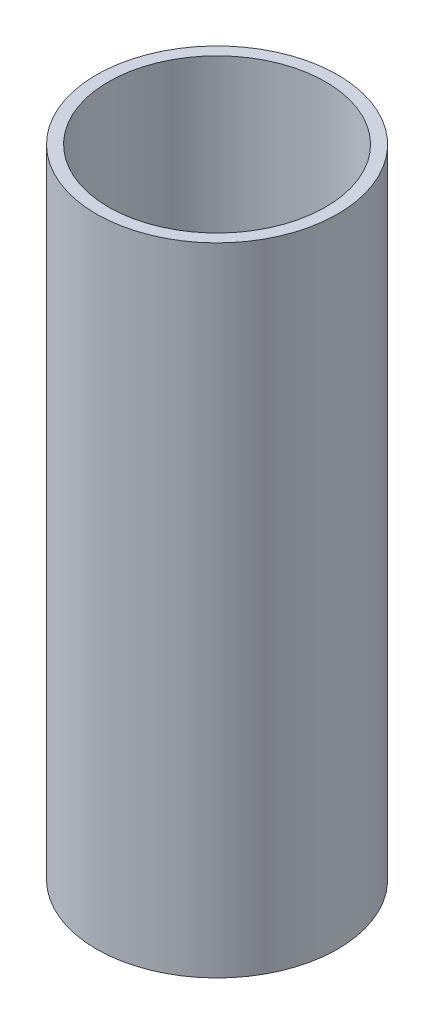
SolidWorks part; units mm, degrees
ref_plane "Front Plane" through (0, 0, 0) normal (0, 0, 1) x (1, 0, 0)
ref_plane "Top Plane" through (0, 0, 0) normal (0, 1, 0) x (1, 0, 0)
ref_plane "Right Plane" through (0, 0, 0) normal (1, 0, 0) x (0, 0, -1)
sketch "Sketch1" plane through (0, 0, 0) normal (0, 1, 0) x (1, 0, 0)
  circle A0 centre (0, 0) radius 57.15
  circle A1 centre (0, 0) radius 51.435
  dimension "D1" = 114.3
  dimension "D2" = 102.87
extrude "Boss-Extrude1" add sketch "Sketch1" along normal mid plane 301.625
